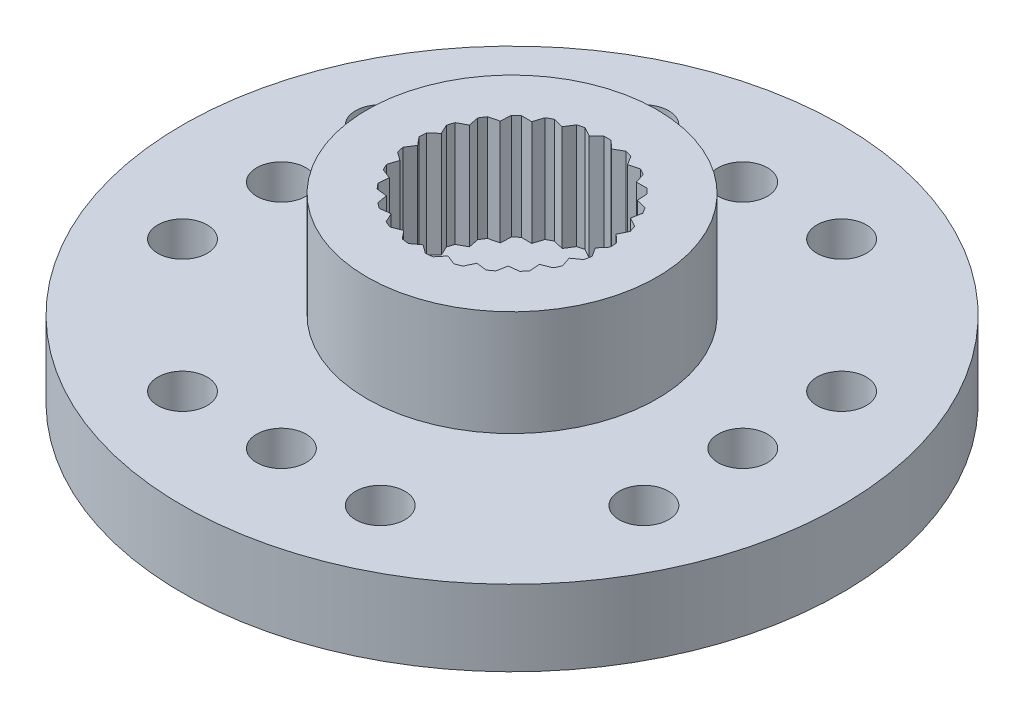
SolidWorks part; units mm, degrees
ref_plane "Front Plane" through (0, 0, 0) normal (0, 0, 1) x (1, 0, 0)
ref_plane "Top Plane" through (0, 0, 0) normal (0, 1, 0) x (1, 0, 0)
ref_plane "Right Plane" through (0, 0, 0) normal (1, 0, 0) x (0, 0, -1)
sketch "Sketch1" plane through (0, 0, 0) normal (0, 0, 1) x (1, 0, 0)
  line L0 (10, 1.15) -> (0, 1.15)
  line L1 (0, 1.15) -> (0, -1.15)
  line L2 (0, -1.15) -> (10, -1.15)
  line L3 (10, -1.15) -> (10, 1.15)
  line L4 (0, 1.15) -> (0, -1.15) construction
revolve "Revolve1" add sketch "Sketch1" angle 360 about L4
sketch "Sketch2" plane through (0, 1.15, 0) normal (0, 1, 0) x (-1, 0, 0)
  circle A0 centre (0, 0) radius 4.4
extrude "Boss-Extrude1" add sketch "Sketch2" along normal blind 3.2
sketch "Sketch3" plane through (0, 4.35, 0) normal (0, 1, 0) x (-1, 0, 0)
  line L0 (-0.6167, -2.8337) -> (-0.3384, -2.6787)
  line L1 (-0.3384, -2.6787) -> (-0.1074, -2.898)
  line L2 (0.1074, -2.898) -> (0.3384, -2.6787)
  line L3 (0.3384, -2.6787) -> (0.6167, -2.8337)
  line L4 (0.8248, -2.7802) -> (0.9939, -2.5104)
  line L5 (0.9939, -2.5104) -> (1.302, -2.5913)
  line L6 (1.4903, -2.4878) -> (1.587, -2.1843)
  line L7 (1.587, -2.1843) -> (1.9055, -2.1861)
  line L8 (2.0621, -2.039) -> (2.0804, -1.721)
  line L9 (2.0804, -1.721) -> (2.3893, -1.6435)
  line L10 (2.5044, -1.4621) -> (2.443, -1.1496)
  line L11 (2.443, -1.1496) -> (2.723, -0.9977)
  line L12 (2.7894, -0.7934) -> (2.6522, -0.5059)
  line L13 (2.6522, -0.5059) -> (2.8855, -0.2892)
  line L14 (2.899, -0.0748) -> (2.6947, 0.1695)
  line L15 (2.6947, 0.1695) -> (2.8668, 0.4375)
  line L16 (2.8265, 0.6486) -> (2.5679, 0.8343)
  line L17 (2.5679, 0.8343) -> (2.6679, 1.1367)
  line L18 (2.5765, 1.3311) -> (2.2797, 1.4467)
  line L19 (2.2797, 1.4467) -> (2.3014, 1.7645)
  line L20 (2.1645, 1.93) -> (1.8483, 1.9682)
  line L21 (1.8483, 1.9682) -> (1.7903, 2.2814)
  line L22 (1.6165, 2.4077) -> (1.3007, 2.366)
  line L23 (1.3007, 2.366) -> (1.1667, 2.655)
  line L24 (0.967, 2.734) -> (0.6715, 2.6152)
  line L25 (0.6715, 2.6152) -> (0.4698, 2.8617)
  line L26 (0.2566, 2.8886) -> (0, 2.7)
  line L27 (0, 2.7) -> (-0.2566, 2.8886)
  line L28 (-0.4698, 2.8617) -> (-0.6715, 2.6152)
  line L29 (-0.6715, 2.6152) -> (-0.967, 2.734)
  line L30 (-1.1667, 2.655) -> (-1.3007, 2.366)
  line L31 (-1.3007, 2.366) -> (-1.6165, 2.4077)
  line L32 (-1.7903, 2.2814) -> (-1.8483, 1.9682)
  line L33 (-1.8483, 1.9682) -> (-2.1645, 1.93)
  line L34 (-2.3014, 1.7645) -> (-2.2797, 1.4467)
  line L35 (-2.2797, 1.4467) -> (-2.5765, 1.3311)
  line L36 (-2.6679, 1.1367) -> (-2.5679, 0.8343)
  line L37 (-2.5679, 0.8343) -> (-2.8265, 0.6486)
  line L38 (-2.8668, 0.4375) -> (-2.6947, 0.1695)
  line L39 (-2.6947, 0.1695) -> (-2.899, -0.0748)
  line L40 (-2.8855, -0.2892) -> (-2.6522, -0.5059)
  line L41 (-2.6522, -0.5059) -> (-2.7894, -0.7934)
  line L42 (-2.723, -0.9977) -> (-2.443, -1.1496)
  line L43 (-2.443, -1.1496) -> (-2.5044, -1.4621)
  line L44 (-2.3893, -1.6435) -> (-2.0804, -1.721)
  line L45 (-2.0804, -1.721) -> (-2.0621, -2.039)
  line L46 (-1.9055, -2.1861) -> (-1.587, -2.1843)
  line L47 (-1.587, -2.1843) -> (-1.4903, -2.4878)
  line L48 (-1.302, -2.5913) -> (-0.9939, -2.5104)
  line L49 (-0.9939, -2.5104) -> (-0.8248, -2.7802)
  arc A0 (-0.8248, -2.7802) -> (-0.6167, -2.8337) centre (0, 0) ccw
  arc A1 (-0.1074, -2.898) -> (0.1074, -2.898) centre (0, 0) ccw
  arc A2 (0.6167, -2.8337) -> (0.8248, -2.7802) centre (0, 0) ccw
  arc A3 (1.302, -2.5913) -> (1.4903, -2.4878) centre (0, 0) ccw
  arc A4 (1.9055, -2.1861) -> (2.0621, -2.039) centre (0, 0) ccw
  arc A5 (2.3893, -1.6435) -> (2.5044, -1.4621) centre (0, 0) ccw
  arc A6 (2.723, -0.9977) -> (2.7894, -0.7934) centre (0, 0) ccw
  arc A7 (2.8855, -0.2892) -> (2.899, -0.0748) centre (0, 0) ccw
  arc A8 (2.8668, 0.4375) -> (2.8265, 0.6486) centre (0, 0) ccw
  arc A9 (2.6679, 1.1367) -> (2.5765, 1.3311) centre (0, 0) ccw
  arc A10 (2.3014, 1.7645) -> (2.1645, 1.93) centre (0, 0) ccw
  arc A11 (1.7903, 2.2814) -> (1.6165, 2.4077) centre (0, 0) ccw
  arc A12 (1.1667, 2.655) -> (0.967, 2.734) centre (0, 0) ccw
  arc A13 (0.4698, 2.8617) -> (0.2566, 2.8886) centre (0, 0) ccw
  arc A14 (-0.2566, 2.8886) -> (-0.4698, 2.8617) centre (0, 0) ccw
  arc A15 (-0.967, 2.734) -> (-1.1667, 2.655) centre (0, 0) ccw
  arc A16 (-1.6165, 2.4077) -> (-1.7903, 2.2814) centre (0, 0) ccw
  arc A17 (-2.1645, 1.93) -> (-2.3014, 1.7645) centre (0, 0) ccw
  arc A18 (-2.5765, 1.3311) -> (-2.6679, 1.1367) centre (0, 0) ccw
  arc A19 (-2.8265, 0.6486) -> (-2.8668, 0.4375) centre (0, 0) ccw
  arc A20 (-2.899, -0.0748) -> (-2.8855, -0.2892) centre (0, 0) ccw
  arc A21 (-2.7894, -0.7934) -> (-2.723, -0.9977) centre (0, 0) ccw
  arc A22 (-2.5044, -1.4621) -> (-2.3893, -1.6435) centre (0, 0) ccw
  arc A23 (-2.0621, -2.039) -> (-1.9055, -2.1861) centre (0, 0) ccw
  arc A24 (-1.4903, -2.4878) -> (-1.302, -2.5913) centre (0, 0) ccw
extrude "Cut-Extrude1" cut sketch "Sketch3" against normal blind 3.2
hole_wizard "Ø1.5 (1.5) Diameter Hole1" positions "Sketch5" profile "Sketch4" hole size "Ø1.5" standard "ANSI Metric"
sketch "Sketch5" plane through (0, -1.15, 0) normal (0, -1, 0) x (-1, 0, 0)
  point P0 (0, 7)
  point P1 (3, 7)
  point P2 (-3, 7)
  point P3 (-7, 0)
  point P4 (-7, 3)
  point P5 (-7, -3)
  point P6 (0, -7)
  point P7 (-3, -7)
  point P8 (3, -7)
  point P9 (7, 0)
  point P10 (7, -3)
  point P11 (7, 3)
sketch "Sketch4" plane through (0, -1.15, -7) normal (1, 0, 0) x (0, 0, -1)
  line L0 (0, 0) -> (0, 5.5)
  line L1 (0, 5.5) -> (0.75, 5.5)
  line L2 (0.75, 5.5) -> (0.75, 0)
  line L5 (0.75, 0) -> (0, 0)
  line L11 (0, -6.35) -> (0, 107.95) construction
  dimension "Thru Hole Dia." = 1.5
  dimension "Thru Hole Depth" = 5.5
hole_wizard "Ø3.0 (3) Diameter Hole1" positions "Sketch7" profile "Sketch6" hole size "Ø3.0" standard "ANSI Metric"
sketch "Sketch7" plane through (0, -1.15, 0) normal (0, -1, 0) x (-1, 0, 0)
  point P0 (0, 0)
sketch "Sketch6" plane through (0, -1.15, 0) normal (1, 0, 0) x (0, 0, -1)
  line L0 (0, 0) -> (0, 5.5)
  line L1 (0, 5.5) -> (1.5, 5.5)
  line L2 (1.5, 5.5) -> (1.5, 0)
  line L5 (1.5, 0) -> (0, 0)
  line L11 (0, -6.35) -> (0, 107.95) construction
  dimension "Thru Hole Dia." = 3
  dimension "Thru Hole Depth" = 5.5
